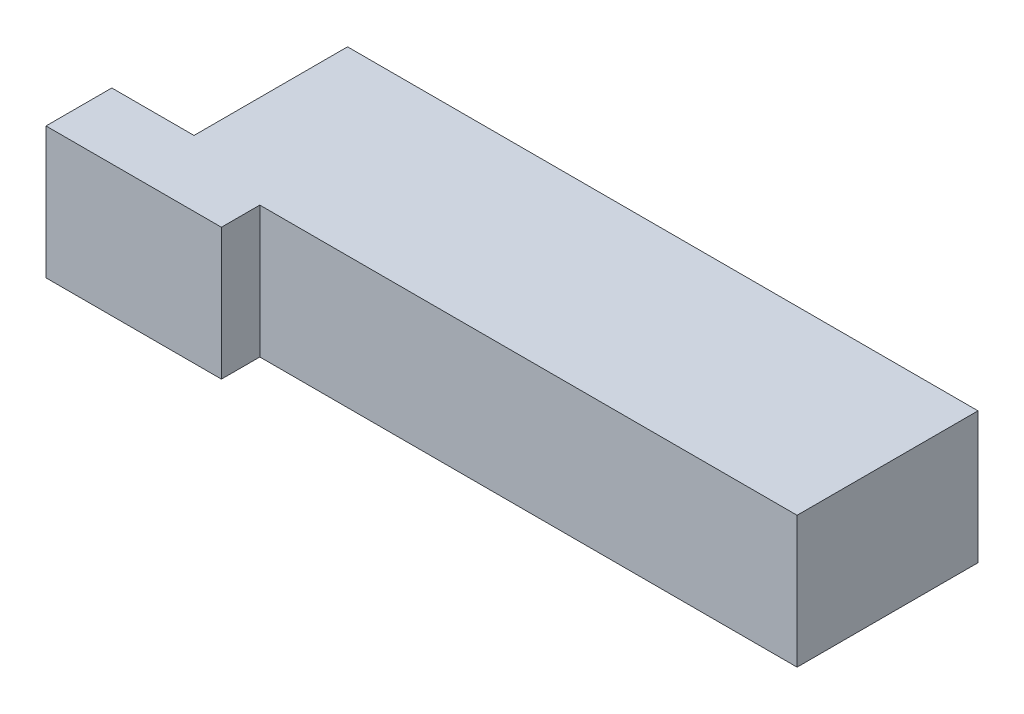
SolidWorks part; units mm, degrees
ref_plane "Front Plane" through (0, 0, 0) normal (0, 0, 1) x (1, 0, 0)
ref_plane "Top Plane" through (0, 0, 0) normal (0, 1, 0) x (1, 0, 0)
ref_plane "Right Plane" through (0, 0, 0) normal (1, 0, 0) x (0, 0, -1)
sketch "Sketch1" plane through (0, 0, 0) normal (0, 1, 0) x (1, 0, 0)
  line L1 (-57.5, -16.5) -> (57.5, -16.5)
  line L2 (-57.5, -16.5) -> (-57.5, 16.5)
  line L3 (-57.5, 16.5) -> (57.5, 16.5)
  line L4 (57.5, -16.5) -> (57.5, 16.5)
  line L5 (-57.5, -16.5) -> (57.5, 16.5) construction
  line L6 (-57.5, 16.5) -> (57.5, -16.5) construction
  point P0 (0, 0)
  dimension "D1" = 115
  dimension "D2" = 33
extrude "Boss-Extrude1" add sketch "Sketch1" along normal blind 24
sketch "Sketch2" plane through (-57.5, 0, 0) normal (-1, 0, 0) x (0, 0, 1)
  line L0 (-16.5, 0) -> (16.5, 0) construction
  line L1 (16.5, 24) -> (11.5, 24)
  line L2 (16.5, 24) -> (16.5, 0)
  line L3 (16.5, 0) -> (11.5, 0)
  line L4 (11.5, 24) -> (11.5, 0)
  dimension "D1" = 5
extrude "Boss-Extrude2" add sketch "Sketch2" along normal blind 15
sketch "Sketch3" plane through (0, 0, 16.5) normal (0, 0, 1) x (1, 0, 0)
  line L0 (-72.5, 0) -> (57.5, 0) construction
  line L1 (-72.5, 24) -> (-40.5, 24)
  line L2 (-72.5, 24) -> (-72.5, 0)
  line L3 (-72.5, 0) -> (-40.5, 0)
  line L4 (-40.5, 24) -> (-40.5, 0)
  line L5 (-57.5, 24) -> (-57.5, 0) construction
  line L6 (-57.5, 24) -> (-57.5, 0)
  line M4 (-72.5, 0) -> (57.5, 0)
  line M6 (57.5, 24) -> (-72.5, 24)
  line M7 (-72.5, 24) -> (-72.5, 0)
  dimension "D1" = 17
extrude "Boss-Extrude3" add sketch "Sketch3" along normal blind 7 contours L6 L3 L4 M6 | L6 L1 M7 M4
